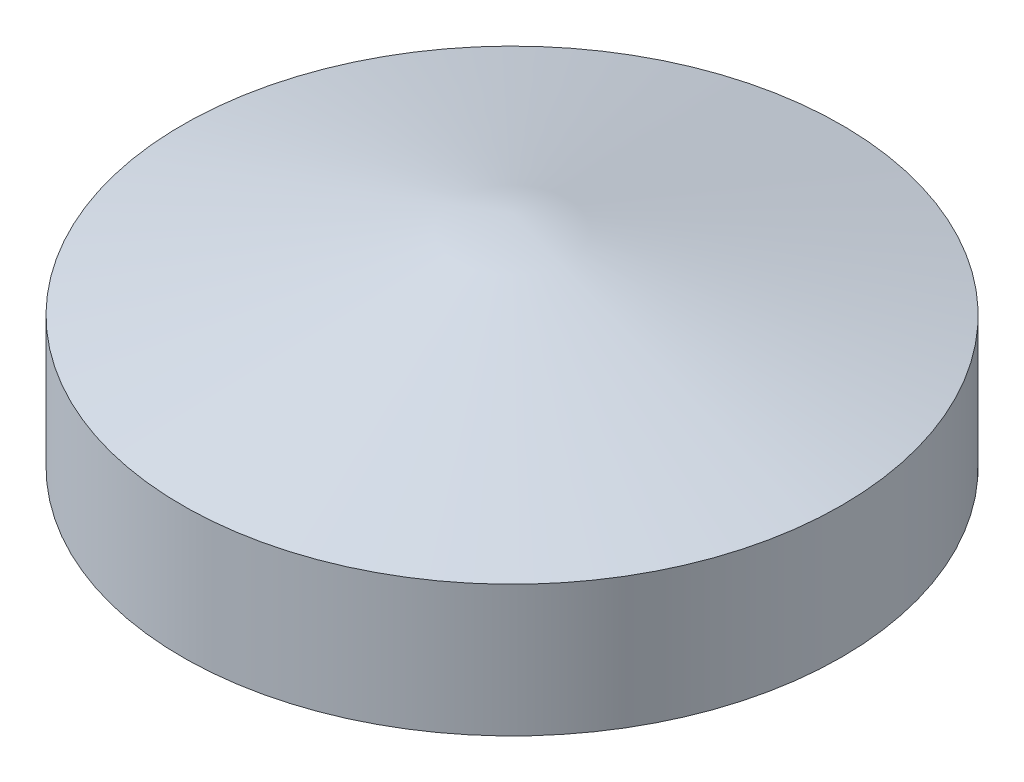
SolidWorks part; units mm, degrees
ref_plane "Спереди" through (0, 0, 0) normal (0, 0, 1) x (1, 0, 0)
ref_plane "Сверху" through (0, 0, 0) normal (0, 1, 0) x (1, 0, 0)
ref_plane "Справа" through (0, 0, 0) normal (1, 0, 0) x (0, 0, -1)
sketch "Эскиз1" plane through (0, 0, 0) normal (0, 0, 1) x (1, 0, 0)
  line L0 (0, 0) -> (0, 3.5885)
  line L1 (0, 3.5885) -> (-9, 1.1769)
  line L2 (0, 0) -> (-9, -2.4115)
  line L3 (-9, -2.4115) -> (-9, 1.1769)
  dimension "D1" = 75
  dimension "D2" = 9
  dimension "D3" = 6
revolve "Повернуть1" add sketch "Эскиз1" angle 360 about L0
